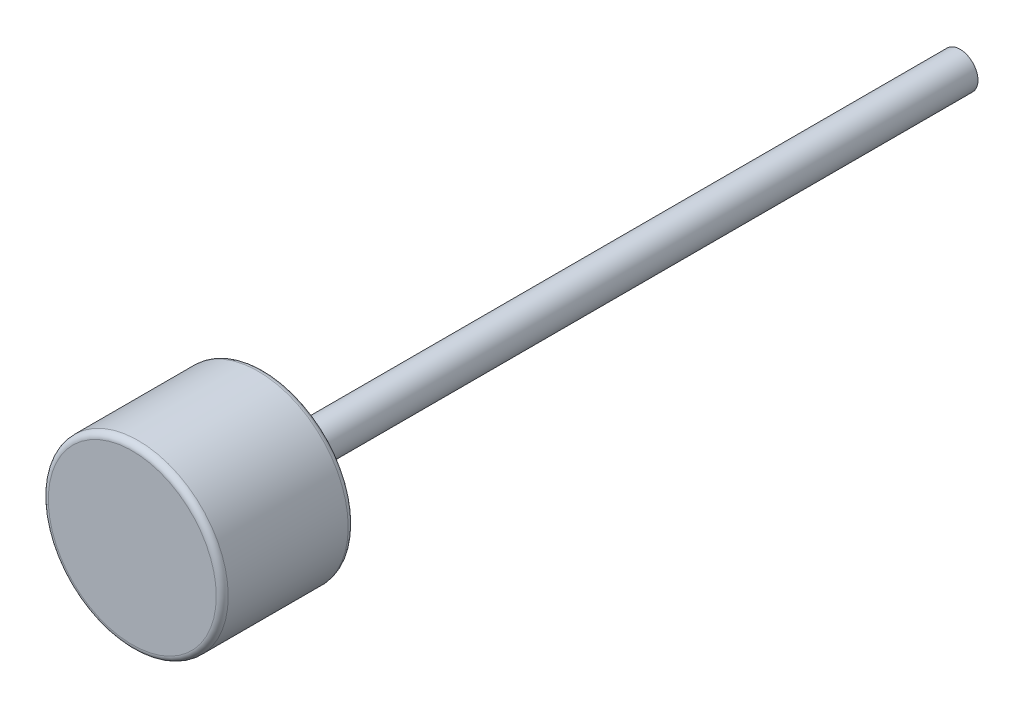
SolidWorks part; units mm, degrees
ref_plane "前视基准面" through (0, 0, 0) normal (0, 0, 1) x (1, 0, 0)
ref_plane "上视基准面" through (0, 0, 0) normal (0, 1, 0) x (1, 0, 0)
ref_plane "右视基准面" through (0, 0, 0) normal (1, 0, 0) x (0, 0, -1)
other "Configuration Table"
sketch "草图1" plane through (0, 0, 0) normal (0, 0, 1) x (1, 0, 0)
  circle A0 centre (0, 0) radius 7.5
  dimension "D1" = 15
extrude "凸台-拉伸1" add sketch "草图1" along normal blind 11
fillet "圆角1" radius 0.5 2 edges at (7.5, 0, 0) (7.5, 0, 11)
sketch "草图2" plane through (0, 0, 0) normal (0, 0, -1) x (-1, 0, 0)
  circle A0 centre (0, 0) radius 1.5
  dimension "D1" = 3
extrude "凸台-拉伸2" add sketch "草图2" along normal blind 58
cosmetic thread "装饰螺纹线1" parameters "D1"=5, "D2"=0.3
